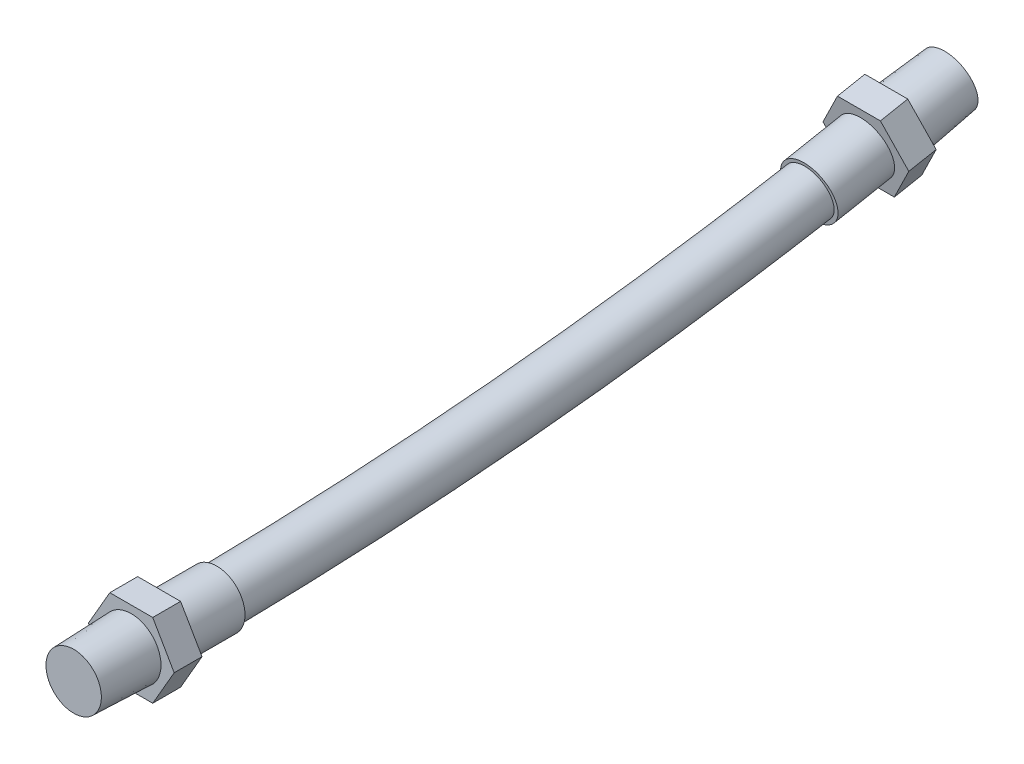
SolidWorks part; units mm, degrees
material "AISI 304"
ref_plane "Front Plane" through (0, 0, 0) normal (0, 0, 1) x (1, 0, 0)
ref_plane "Top Plane" through (0, 0, 0) normal (0, 1, 0) x (1, 0, 0)
ref_plane "Right Plane" through (0, 0, 0) normal (1, 0, 0) x (0, 0, -1)
sketch "Sketch1" plane through (0, 0, 0) normal (1, 0, 0) x (0, 0, -1)
  line L0 (-1000, 0) -> (49000, 0) construction
  arc A0 (0, 0) -> (120.7633, 11.43) centre (0, 643.6752) ccw
  dimension "D1" = 120.7633
  dimension "D2" = 11.43
sketch "Sketch2" plane through (0, 0, 0) normal (0, 0, 1) x (1, 0, 0)
  circle A0 centre (0, 0) radius 4.191
  dimension "D1" = 8.382
sweep "Sweep1" add profiles "Sketch2" path "Sketch1"
sketch "Sketch3" plane through (0, 0, 0) normal (0, 0, 1) x (1, 0, 0)
  line L1 (7.3323, 0) -> (3.6662, 6.35)
  line L2 (3.6662, 6.35) -> (-3.6662, 6.35)
  line L3 (-3.6662, 6.35) -> (-7.3323, 0)
  line L4 (-7.3323, 0) -> (-3.6662, -6.35)
  line L5 (-3.6662, -6.35) -> (3.6662, -6.35)
  line L6 (3.6662, -6.35) -> (7.3323, 0)
  circle A0 centre (0, 0) radius 6.35 construction
  dimension "D1" = 12.7
extrude "Boss-Extrude1" add sketch "Sketch3" along normal blind 4.7625
sketch "Sketch4" plane through (0, 0, 4.7625) normal (0, 0, 1) x (1, 0, 0)
  circle A0 centre (0, 0) radius 5.08
  dimension "D1" = 10.16
extrude "Boss-Extrude2" add sketch "Sketch4" along normal blind 9.8425 draft 2
sketch "Sketch6" plane through (0, 0, 0) normal (0, 0, -1) x (-1, 0, 0)
  circle A0 centre (0, 0) radius 4.191 construction
  circle A3 centre (0, 0) radius 4.826
  dimension "D1" = 0.635
extrude "Boss-Extrude3" add sketch "Sketch6" along normal blind 9.8425
sketch "Sketch5" plane through (0, 0, 0) normal (1, 0, 0) x (0, 0, -1)
  line L3 (0, 643.6752) -> (0, 0) construction
  line L4 (0, 0) -> (120.7633, 11.43) construction
  line L5 (121.5496, 7.3134) -> (119.977, 15.5466) construction
  line L6 (120.7633, 11.43) -> (0, 643.6752) construction
  line L7 (60.3816, 5.715) -> (0, 643.6752)
  circle A0 centre (0, 643.6752) radius 643.6752 construction
  arc A1 (0, 0) -> (120.7633, 11.43) centre (0, 643.6752) ccw construction
ref_plane "Plane1" through (0, 5.715, -60.3816) normal (0, 0.0942, -0.9956) x (0, 0.9956, 0.0942)
mirror "Mirror1" about plane through (0, 5.715, -60.3816) normal (0, 0.0942, -0.9956) of "Boss-Extrude3", "Boss-Extrude2", "Boss-Extrude1"
